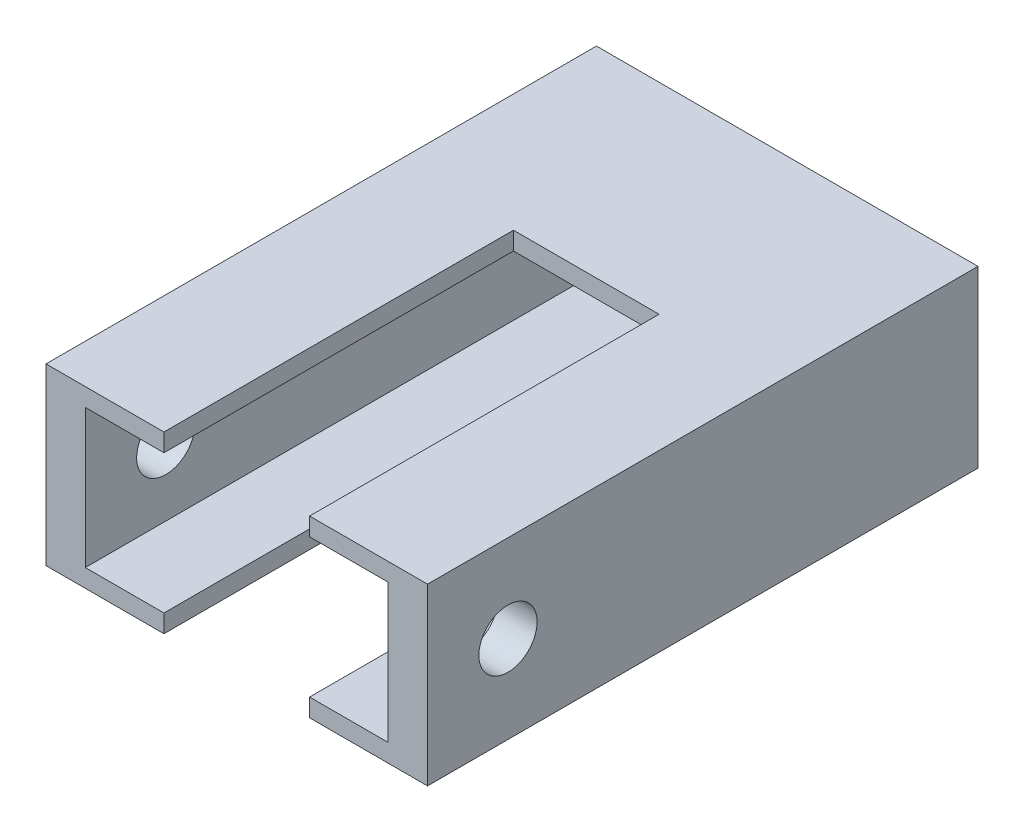
SolidWorks part; units mm, degrees
ref_plane "Front Plane" through (0, 0, 0) normal (0, 0, 1) x (1, 0, 0)
ref_plane "Top Plane" through (0, 0, 0) normal (0, 1, 0) x (1, 0, 0)
ref_plane "Right Plane" through (0, 0, 0) normal (1, 0, 0) x (0, 0, -1)
sketch "Sketch2" plane through (0, 0, 0) normal (0, 0, 1) x (1, 0, 0)
  line L1 (-32.75, 15) -> (32.75, 15)
  line L2 (-32.75, 15) -> (-32.75, -15)
  line L3 (-32.75, -15) -> (32.75, -15)
  line L4 (32.75, 15) -> (32.75, -15)
  line L5 (-32.75, 15) -> (32.75, -15) construction
  line L6 (-32.75, -15) -> (32.75, 15) construction
  line L7 (-26, 11.9084) -> (26, 11.9084)
  line L8 (-26, 11.9084) -> (-26, -11.9084)
  line L9 (-26, -11.9084) -> (26, -11.9084)
  line L10 (26, 11.9084) -> (26, -11.9084)
  line L11 (-26, 11.9084) -> (26, -11.9084) construction
  line L12 (-26, -11.9084) -> (26, 11.9084) construction
  point P0 (0, 0)
  point P6 (0, 0)
  dimension "D1" = 65.5
  dimension "D2" = 30
  dimension "D3" = 52
extrude "Boss-Extrude1" add sketch "Sketch2" along normal blind 94.5 contours L8 L7 L10 L9 | L2 L1 L4 L3
sketch "Sketch3" plane through (0, 0, 0) normal (0, 0, -1) x (-1, 0, 0)
  line L1 (-26, 11.9084) -> (26, 11.9084)
  line L2 (-26, 11.9084) -> (-26, -11.9084)
  line L3 (-26, -11.9084) -> (26, -11.9084)
  line L4 (26, 11.9084) -> (26, -11.9084)
  line L5 (-26, 11.9084) -> (26, -11.9084) construction
  line L6 (-26, -11.9084) -> (26, 11.9084) construction
  point P0 (0, 0)
extrude "Boss-Extrude2" add sketch "Sketch3" against normal blind 10
sketch "Sketch4" plane through (0, 0, 94.5) normal (0, 0, 1) x (1, 0, 0)
  line L0 (-32.75, -15) -> (32.75, -15) construction
  line L1 (-12.5, 15) -> (12.5, 15)
  line L2 (-12.5, 15) -> (-12.5, -15)
  line L3 (-12.5, -15) -> (12.5, -15)
  line L4 (12.5, 15) -> (12.5, -15)
  line L5 (-12.5, 15) -> (12.5, -15) construction
  line L6 (-12.5, -15) -> (12.5, 15) construction
  point P0 (0, 0)
  dimension "D1" = 25
extrude "Cut-Extrude1" cut sketch "Sketch4" against normal blind 60
sketch "Sketch5" plane through (-32.75, 0, 0) normal (-1, 0, 0) x (0, 0, 1)
  circle A0 centre (80.6908, 0) radius 5
  dimension "D1" = 10
extrude "Cut-Extrude2" cut sketch "Sketch5" against normal through all
sketch "Sketch6" plane through (0, 0, 0) normal (0, 0, -1) x (-1, 0, 0)
  circle A0 centre (0, 0) radius 5
  dimension "D1" = 10
extrude "Cut-Extrude3" cut sketch "Sketch6" against normal through all
